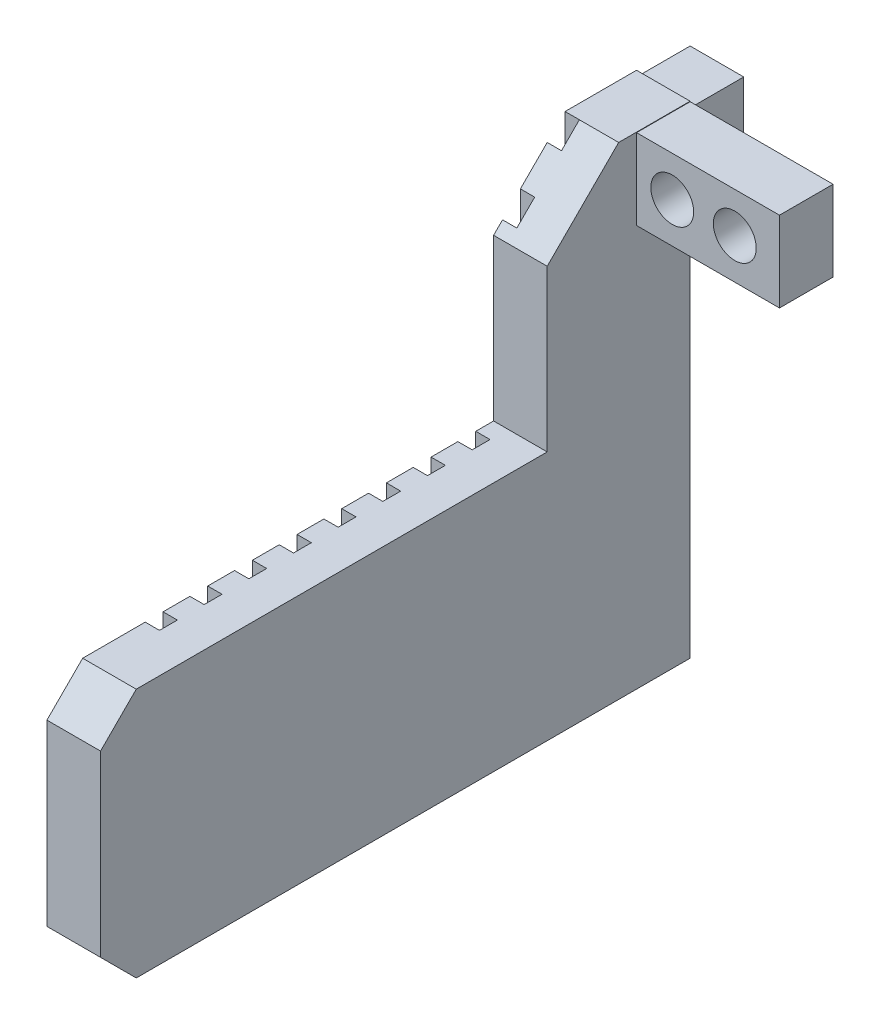
SolidWorks part; units mm, degrees
ref_plane "Front Plane" through (0, 0, 0) normal (0, 0, 1) x (1, 0, 0)
ref_plane "Top Plane" through (0, 0, 0) normal (0, 1, 0) x (1, 0, 0)
ref_plane "Right Plane" through (0, 0, 0) normal (1, 0, 0) x (0, 0, -1)
sketch "Sketch1" plane through (0, 0, 0) normal (0, 0, 1) x (1, 0, 0)
  line L0 (10, -7) -> (13, -7)
  line L1 (13, -7) -> (13, 20)
  line L2 (13, 20) -> (10, 20)
  line L3 (10, 20) -> (10, -7)
extrude "Boss-Extrude1" add sketch "Sketch1" along normal blind 8 from offset 25
sketch "Sketch2" plane through (0, 0, 0) normal (0, 0, 1) x (1, 0, 0)
  line L0 (10, -7) -> (13, -7)
  line L1 (13, -7) -> (13, 7)
  line L2 (13, 7) -> (10, 7)
  line L3 (10, 7) -> (10, -7)
extrude "Boss-Extrude2" add sketch "Sketch2" along normal blind 25.5 from offset 32.5
sketch "Sketch3" plane through (0, 0, 0) normal (0, 0, 1) x (1, 0, 0)
  line L0 (13, 15.475) -> (21, 15.475)
  line L1 (21, 15.475) -> (21, 19.975)
  line L2 (21, 19.975) -> (13, 19.975)
  line L3 (13, 19.975) -> (13, 15.475)
extrude "Boss-Extrude3" add sketch "Sketch3" along normal blind 3 from offset 25
sketch "Sketch4" plane through (0, 0, 0) normal (0, 0, 1) x (1, 0, 0)
  line L0 (10, 15.775) -> (13, 15.775)
  line L1 (13, 15.775) -> (13, 19.675)
  line L2 (13, 19.675) -> (10, 19.675)
  line L3 (10, 19.675) -> (10, 15.775)
extrude "Boss-Extrude4" add sketch "Sketch4" along normal blind 3 from offset 22
sketch "Sketch5" plane through (0, 0, 0) normal (0, 0, 1) x (1, 0, 0)
  circle A0 centre (15, 17.725) radius 1.2
  circle A1 centre (18.5, 17.725) radius 1.2
extrude "Cut-Extrude1" cut sketch "Sketch5" against normal through all and the other way through all
sketch "Sketch6" plane through (0, 0, 0) normal (0, 1, 0) x (1, 0, 0)
  line L0 (9, -29) -> (10.8, -29)
  line L1 (10.8, -29) -> (10.8, -30)
  line L2 (10.8, -30) -> (9, -30)
  line L3 (9, -30) -> (9, -29)
  line L4 (9, -31.5) -> (10.8, -31.5)
  line L5 (10.8, -31.5) -> (10.8, -32.5)
  line L6 (10.8, -32.5) -> (9, -32.5)
  line L7 (9, -32.5) -> (9, -31.5)
  line L8 (9, -34) -> (10.8, -34)
  line L9 (10.8, -34) -> (10.8, -35)
  line L10 (10.8, -35) -> (9, -35)
  line L11 (9, -35) -> (9, -34)
  line L12 (9, -36.5) -> (10.8, -36.5)
  line L13 (10.8, -36.5) -> (10.8, -37.5)
  line L14 (10.8, -37.5) -> (9, -37.5)
  line L15 (9, -37.5) -> (9, -36.5)
  line L16 (9, -39) -> (10.8, -39)
  line L17 (10.8, -39) -> (10.8, -40)
  line L18 (10.8, -40) -> (9, -40)
  line L19 (9, -40) -> (9, -39)
  line L20 (9, -41.5) -> (10.8, -41.5)
  line L21 (10.8, -41.5) -> (10.8, -42.5)
  line L22 (10.8, -42.5) -> (9, -42.5)
  line L23 (9, -42.5) -> (9, -41.5)
  line L24 (9, -44) -> (10.8, -44)
  line L25 (10.8, -44) -> (10.8, -45)
  line L26 (10.8, -45) -> (9, -45)
  line L27 (9, -45) -> (9, -44)
  line L28 (9, -46.5) -> (10.8, -46.5)
  line L29 (10.8, -46.5) -> (10.8, -47.5)
  line L30 (10.8, -47.5) -> (9, -47.5)
  line L31 (9, -47.5) -> (9, -46.5)
  line L32 (9, -49) -> (10.8, -49)
  line L33 (10.8, -49) -> (10.8, -50)
  line L34 (10.8, -50) -> (9, -50)
  line L35 (9, -50) -> (9, -49)
  line L36 (9, -51.5) -> (10.8, -51.5)
  line L37 (10.8, -51.5) -> (10.8, -52.5)
  line L38 (10.8, -52.5) -> (9, -52.5)
  line L39 (9, -52.5) -> (9, -51.5)
extrude "Cut-Extrude2" cut sketch "Sketch6" against normal through all and the other way through all
sketch "Sketch7" plane through (0, 0, 0) normal (1, 0, 0) x (0, 0, -1)
  line L0 (-55.3, -7.7) -> (-59, -7.7)
  line L1 (-59, -7.7) -> (-59, -4)
  line L2 (-59, -4) -> (-55.3, -7.7)
  line L3 (-55.3, 7.7) -> (-59, 4)
  line L4 (-59, 4) -> (-59, 7.7)
  line L5 (-59, 7.7) -> (-55.3, 7.7)
  line L6 (-28, 21) -> (-34, 21)
  line L7 (-34, 21) -> (-34, 15)
  line L8 (-34, 15) -> (-28, 21)
extrude "Cut-Extrude3" cut sketch "Sketch7" against normal through all and the other way through all
